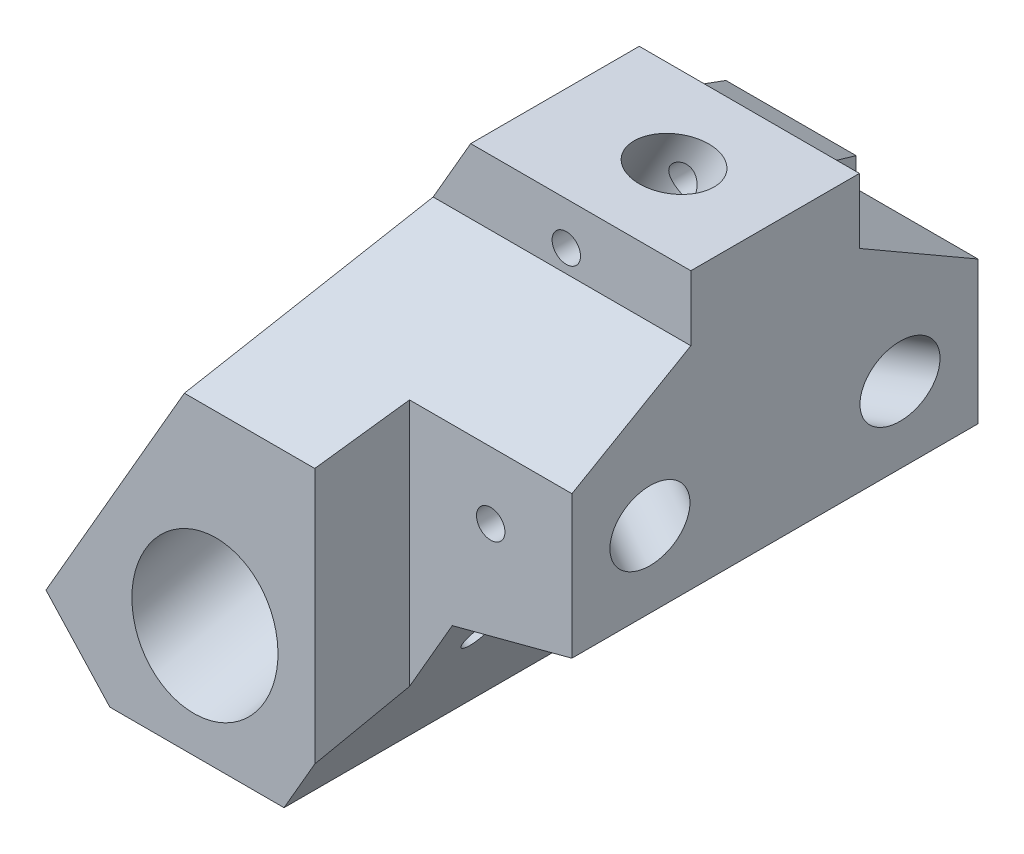
SolidWorks part; units mm, degrees
material "Acrylic (Medium-high impact)"
ref_plane "Front Plane" through (0, 0, 0) normal (0, 0, 1) x (1, 0, 0)
ref_plane "Top Plane" through (0, 0, 0) normal (0, 1, 0) x (1, 0, 0)
ref_plane "Right Plane" through (0, 0, 0) normal (1, 0, 0) x (0, 0, -1)
sketch "Sketch1" plane through (0, 0, 0) normal (0, 1, 0) x (1, 0, 0)
  line L0 (0, 0) -> (86.6025, 50) construction
  line L1 (0, 0) -> (86.6025, -50) construction
  line L2 (0, 0) -> (45.8659, 0) construction
  line L3 (0, 0) -> (-25.8626, 84.5927) construction
  line L4 (0, 0) -> (-18.7896, -61.4579) construction
  line L5 (0, 0) -> (0, -66.7072) construction
  point P5 (86.6025, 50)
  point P6 (86.6025, -50)
  dimension "D1" = 60
  dimension "D2" = 100
  dimension "D3" = 100
  dimension "D4" = 30
  dimension "D5" = 77
  dimension "D6" = 77
  dimension "D7" = 17
ref_plane "Plane1" through (0, 0, 0) normal (0.866, 0, -0.5) x (-0.5, 0, -0.866)
ref_plane "Plane2" through (0, 0, 0) normal (0.866, 0, 0.5) x (0.5, 0, -0.866)
sketch3d "3DSketch1"
  line L0 (0, 0, 0) -> (14.9193, 25.841, 0) construction
  line L1 (0, 0, 0) -> (34.5167, 0, 19.9282) construction
  line L2 (14.9193, 0, 0) -> (14.9193, 27.4134, 0) construction
  line L3 (0, 0, 0) -> (40.2147, 0, 0) construction
  line L4 (0, 0, 0) -> (26.9068, 0, -15.5347) construction
  line L5 (0, 0, 0) -> (86.6025, 0, -50) construction
  line L7 (0, 0, 0) -> (45.8659, 0, 0) construction
  line L8 (0, 0, 0) -> (86.6025, 0, 50) construction
  dimension "D1" = 60
ref_plane "Plane3" through (0, 0, 0) normal (0.5, 0.866, 0) x (0.8582, -0.4955, -0.1345)
sketch3d "3DSketch2"
  line L0 (0, 0, 0) -> (-58.5226, -135.4905, -228.2823) construction
  line L1 (-9.2221, -21.3509, -35.9732) -> (-14.4617, 0, -47.3021) construction
  line L2 (0, 0, 0) -> (86.6025, 0, -50) construction
  line L6 (0, 0, 0) -> (-25.8626, 0, -84.5927) construction
  point P0 (-3.2293, -7.4764, -12.5966)
  dimension "D3" = 15
  dimension "D2" = 30
ref_plane "Plane4" through (0, 0, 0) normal (-0.2153, -0.4984, -0.8398) x (-0.9697, 0.0078, 0.244)
sketch3d "3DSketch3"
  line L1 (-25.8671, 0, 84.6074) -> (-25.8671, -51.0801, 84.6074) construction
  line L2 (0, 0, 0) -> (0, -91.9455, 0) construction
  line L4 (0, 0, 0) -> (-18.7896, 0, 61.4579) construction
  line L5 (-25.8671, -51.0801, 84.6074) -> (0, 0, 0) construction
  dimension "D1" = 30
ref_plane "Plane5" through (0, 0, 0) normal (0.2532, 0.5, -0.8282) x (-0.9674, 0.1309, -0.2168)
sketch "Sketch9" plane through (0, 0, 0) normal (0, 1, 0) x (1, 0, 0)
  line L0 (-5, 50) -> (5, 50)
  line L1 (-60, 50) -> (-60, -50)
  line L2 (-60, 50) -> (-5, 50)
  line L3 (40, -37.5) -> (40, 37.5)
  line L4 (-60, -50) -> (-5, -50)
  line L5 (10, -37.5) -> (40, -37.5)
  line L6 (0, 0) -> (45.8659, 0) construction
  line L7 (40, 37.5) -> (10, 37.5)
  line L8 (5, 50) -> (10, 37.5)
  line L9 (-5, -50) -> (5, -50)
  line L10 (5, -50) -> (10, -37.5)
  dimension "D1" = 60
  dimension "D2" = 100
  dimension "D3" = 55
  dimension "D4" = 55
  dimension "D5" = 75
  dimension "D6" = 5
  dimension "D7" = 30
  dimension "D8" = 40
  dimension "D9" = 50
  dimension "D10" = 10
  dimension "D11" = 10
  dimension "D13" = 37.5
extrude "Boss-Extrude1" add sketch "Sketch9" along normal blind 37 and the other way blind 52
ref_plane "Plane6" through (12.9904, 0, -7.5) normal (0.866, 0, -0.5) x (-0.5, 0, -0.866)
sketch "Sketch11" plane through (12.9904, 0, -7.5) normal (0.866, 0, -0.5) x (-0.5, 0, -0.866)
  circle A0 centre (0, 0) radius 6.4
  dimension "D1" = 12.8
extrude "Cut-Extrude5" cut sketch "Sketch11" along normal up to surface (73.9149 mm away)
ref_plane "Plane7" through (12.9904, 0, 7.5) normal (0.866, 0, 0.5) x (0.5, 0, -0.866)
sketch "Sketch12" plane through (12.9904, 0, 7.5) normal (0.866, 0, 0.5) x (0.5, 0, -0.866)
  circle A0 centre (0, 0) radius 6.4
  dimension "D1" = 12.8
extrude "Cut-Extrude6" cut sketch "Sketch12" along normal through all
ref_plane "Plane8" through (5, 8.6603, 0) normal (0.5, 0.866, 0) x (0.8582, -0.4955, -0.1345)
sketch "Sketch13" plane through (5, 8.6603, 0) normal (0.5, 0.866, 0) x (0.8582, -0.4955, -0.1345)
  circle A0 centre (0, 0) radius 6.4
  dimension "D1" = 12.8
ref_plane "Plane9" through (-3.2293, -7.4764, -12.5966) normal (-0.2153, -0.4984, -0.8398) x (-0.9697, 0.0078, 0.244)
sketch "Sketch14" plane through (-3.2293, -7.4764, -12.5966) normal (-0.2153, -0.4984, -0.8398) x (-0.9697, 0.0078, 0.244)
  circle A0 centre (0, 0) radius 12.9
  dimension "D1" = 25.8
extrude "Cut-Extrude8" cut sketch "Sketch14" along normal through all
ref_plane "Plane10" through (-3.798, -7.5, 12.4228) normal (0.2532, 0.5, -0.8282) x (-0.9674, 0.1309, -0.2168)
sketch "Sketch15" plane through (-3.798, -7.5, 12.4228) normal (0.2532, 0.5, -0.8282) x (-0.9674, 0.1309, -0.2168)
  circle A0 centre (0, 0) radius 12.9
  dimension "D1" = 25.8
extrude "Cut-Extrude9" cut sketch "Sketch15" against normal through all
sketch "Sketch16" plane through (0, 0, -50) normal (0, 0, -1) x (-1, 0, 0)
  line L2 (-40, -52) -> (-40, 37) construction
  line L3 (0, 0) -> (-45.8659, 0) construction
  circle A0 centre (-25, 0) radius 2.625
  dimension "D1" = 5.25
  dimension "D2" = 15
extrude "Cut-Extrude10" cut sketch "Sketch16" against normal through all
extrude "Cut-Extrude15" cut sketch "Sketch13" along normal through all
sketch "Sketch24" plane through (0, 0, -37.5) normal (0, 0, -1) x (-1, 0, 0)
sketch "Sketch25" plane through (0, 0, 50) normal (0, 0, 1) x (1, 0, 0)
  line L0 (-60, -65.7707) -> (-0.6653, 37)
  line L1 (-51.6656, -51.335) -> (-26.8103, -62.0708) construction
  line L2 (-0.6653, 37) -> (-60, 37)
  line L3 (-60, 37) -> (-60, -65.7707)
  line L4 (0, 0) -> (-58.5226, -135.4905) construction
  dimension "D1" = 60
  dimension "D2" = 27.0747
  dimension "D3" = 10
extrude "Cut-Extrude16" cut sketch "Sketch25" against normal through all
sketch "Sketch26" plane through (0, 0, -50) normal (0, 0, -1) x (-1, 0, 0)
  line L0 (-40, -14) -> (-17.8981, -19.8314)
  line L1 (-40, -52) -> (-40, 37) construction
  line L3 (-17.8981, -19.8314) -> (0.6745, -52)
  line L6 (-40, -52) -> (-40, -14)
  line L7 (0.6745, -52) -> (-40, -52)
  line L8 (60, -65.7707) -> (0.6653, 37) construction
  line L11 (-5, -52) -> (52.0495, -52) construction
  line L15 (0.6745, -52) -> (19.035, -44.0695) construction
  line L16 (0, 0) -> (58.5226, -135.4905) construction
  dimension "D1" = 20
  dimension "D2" = 38
extrude "Cut-Extrude17" cut sketch "Sketch26" against normal through all
sketch "Sketch27" plane through (40, 0, 0) normal (-1, 0, 0) x (0, 0, 1)
  line L0 (-50, 37) -> (-15.5987, 37)
  line L1 (-50, 37) -> (50, 37) construction
  line L2 (15.5375, 37) -> (15.5375, 25)
  line L3 (-15.5987, 25) -> (-15.5987, 37)
  line L4 (-50, 5.1384) -> (-50, 37)
  line L7 (50, 5.1031) -> (50, 37)
  line L8 (50, 37) -> (15.5375, 37)
  line L10 (-50, -52) -> (-50, 37) construction
  line L11 (50, -52) -> (50, 37) construction
  line L12 (-15.5987, 25) -> (-50, 5.1384)
  line L13 (15.5375, 25) -> (50, 5.1031)
  line L14 (-15.5987, 25) -> (-50, 25) construction
  line L15 (-50, 25) -> (50, 25) construction
  dimension "D1" = 30
  dimension "D2" = 30
  dimension "D5" = 12
  dimension "D6" = 31.8969
extrude "Cut-Extrude25" cut sketch "Sketch27" along normal through all
sketch "Sketch31" plane through (22.0108, -12.7079, 0) normal (0.866, -0.5, 0) x (0, 0, -1)
  line L0 (-84.6074, -57.1702) -> (0, 0) construction
  line L1 (0, 0) -> (228.2823, -146.5995) construction
  line L4 (-37.5, -8.2254) -> (37.5, -8.2254) construction
  circle A0 centre (-27.7122, -18.7254) radius 2.625
  circle A1 centre (29.1589, -18.7254) radius 2.625
  dimension "D1" = 5.25
  dimension "D2" = 5.25
  dimension "D3" = 10.5
  dimension "D4" = 10.5
extrude "Cut-Extrude22" cut sketch "Sketch31" against normal through all
sketch "Sketch35" plane through (0, 0, -50) normal (0, 0, -1) x (-1, 0, 0)
  line L0 (44.64, -39.1663) -> (25.4615, -60.0338)
  line L1 (52.0495, -52) -> (19.0606, 5.1384) construction
  line L2 (0.6745, -52) -> (52.0495, -52) construction
  line L3 (25.4615, -60.0338) -> (52.0495, -52)
  line L4 (52.0495, -52) -> (44.64, -39.1663)
extrude "Cut-Extrude26" cut sketch "Sketch35" against normal through all
sketch "Sketch36" plane through (0, 0, -15.5987) normal (0, 0, -1) x (-1, 0, 0)
  line L1 (-40, 25) -> (-40, 37) construction
  circle A0 centre (-17, 29.1364) radius 2.625
  point P5 (-40, 31)
  dimension "D1" = 5.25
  dimension "D2" = 23
extrude "Cut-Extrude27" cut sketch "Sketch36" against normal through all
